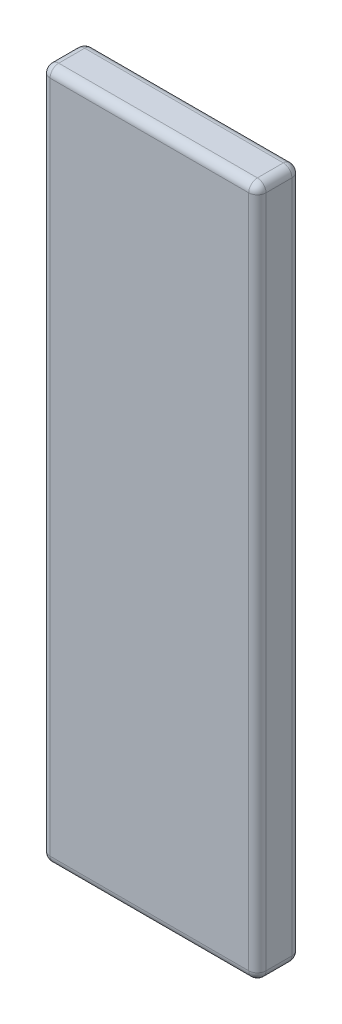
SolidWorks part; units mm, degrees
material "Neodymium (N-35)"
ref_plane "Front Plane" through (0, 0, 0) normal (0, 0, 1) x (1, 0, 0)
ref_plane "Top Plane" through (0, 0, 0) normal (0, 1, 0) x (1, 0, 0)
ref_plane "Right Plane" through (0, 0, 0) normal (1, 0, 0) x (0, 0, -1)
sketch "Sketch1" plane through (0, 0, 0) normal (0, 0, 1) x (1, 0, 0)
  line L1 (-1.25, -4) -> (1.25, -4)
  line L2 (-1.25, -4) -> (-1.25, 4)
  line L3 (-1.25, 4) -> (1.25, 4)
  line L4 (1.25, -4) -> (1.25, 4)
  line L5 (-1.25, -4) -> (1.25, 4) construction
  line L6 (-1.25, 4) -> (1.25, -4) construction
  point P0 (0, 0)
  dimension "D1" = 2.5
  dimension "D2" = 8
extrude "Boss-Extrude1" add sketch "Sketch1" along normal blind 0.5
fillet "Fillet1" radius 0.1 12 edges at (-1.25, 0, 0.5) (1.25, 0, 0.5) (-1.25, -4, 0.25) (0, -4, 0.5) (0, 4, 0.5) (-1.25, 4, 0.25) (1.25, -4, 0.25) (1.25, 4, 0.25) (0, 4, 0) (-1.25, 0, 0) (0, -4, 0) (1.25, 0, 0)
